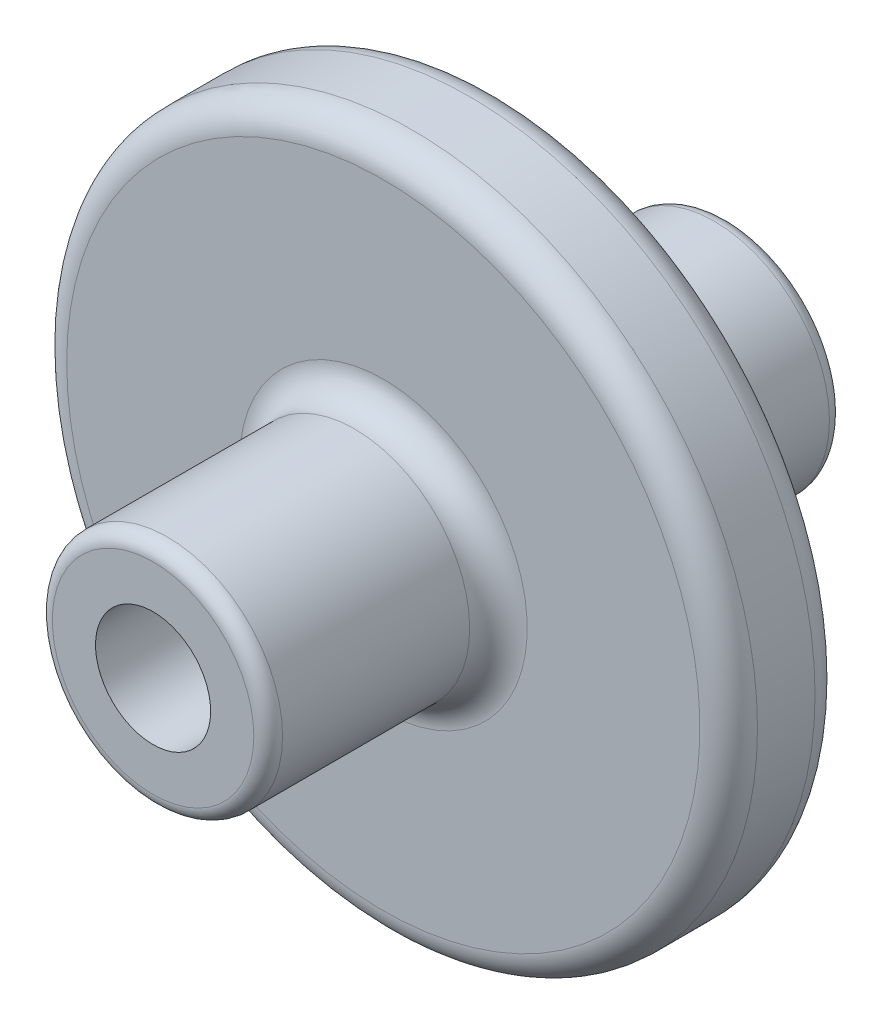
SolidWorks part; units mm, degrees
material "ABS"
ref_plane "Front Plane" through (0, 0, 0) normal (0, 0, 1) x (1, 0, 0)
ref_plane "Top Plane" through (0, 0, 0) normal (0, 1, 0) x (1, 0, 0)
ref_plane "Right Plane" through (0, 0, 0) normal (1, 0, 0) x (0, 0, -1)
sketch "Sketch1" plane through (0, 0, 0) normal (0, 0, 1) x (1, 0, 0)
  circle A0 centre (0, 0) radius 3.175
  circle A1 centre (0, 0) radius 1.5875
  dimension "D1" = 6.35
  dimension "D2" = 3.175
extrude "Boss-Extrude1" add sketch "Sketch1" against normal blind 6.35
sketch "Sketch2" plane through (0, 0, -6.35) normal (0, 0, -1) x (-1, 0, 0)
  circle A0 centre (0, 0) radius 9.525
  circle A1 centre (0, 0) radius 1.5875 construction
  circle A2 centre (0, 0) radius 1.5875
  dimension "D1" = 19.05
extrude "Boss-Extrude2" add sketch "Sketch2" along normal blind 1.5875
mirror "Mirror1" about plane through (0, 0, -7.9375) normal (0, 0, -1) of "Boss-Extrude1", "Boss-Extrude2"
fillet "Fillet1" radius 0.7937 2 edges at (-9.525, 0, -9.525) (-9.525, 0, -6.35)
fillet "Fillet2" radius 0.7937 2 edges at (3.175, 0, -9.525) (3.175, 0, -6.35)
fillet "Fillet3" radius 0.3969 2 edges at (3.175, 0, -15.875) (3.175, 0, 0)
